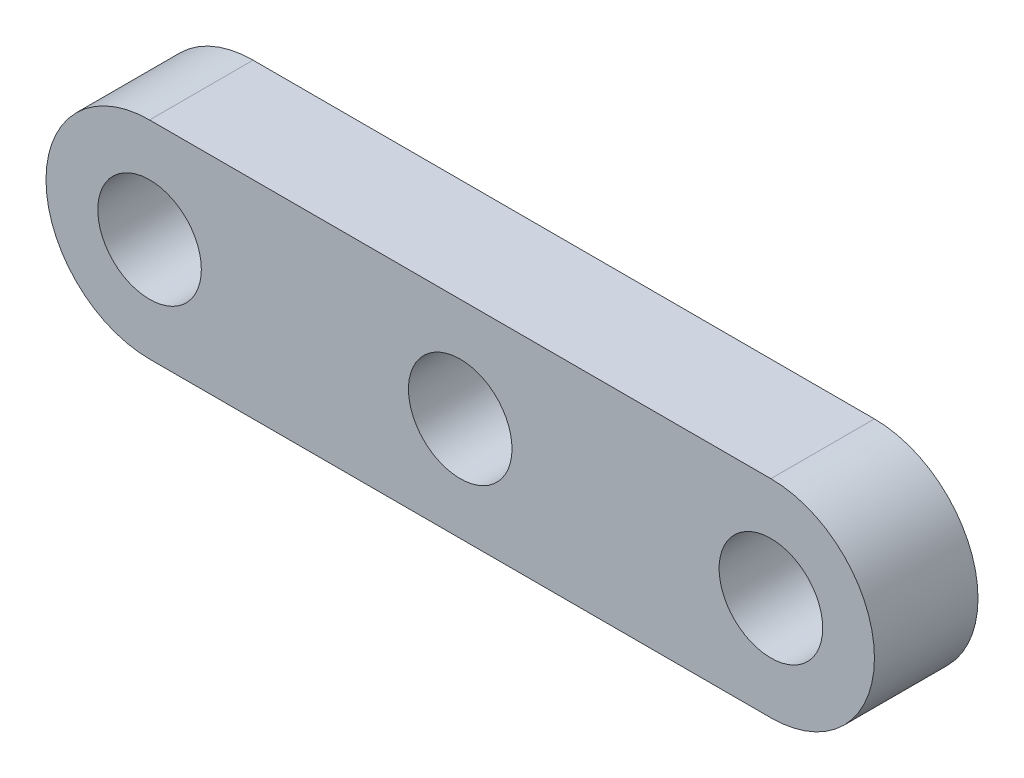
SolidWorks part; units mm, degrees
material "ABS"
ref_plane "Front Plane" through (0, 0, 0) normal (0, 0, 1) x (1, 0, 0)
ref_plane "Top Plane" through (0, 0, 0) normal (0, 1, 0) x (1, 0, 0)
ref_plane "Right Plane" through (0, 0, 0) normal (1, 0, 0) x (0, 0, -1)
sketch "Sketch2" plane through (0, 0, 0) normal (0, 0, 1) x (1, 0, 0)
  line L0 (19.05, 0) -> (-19.05, 0) construction
  line L1 (19.05, -6.35) -> (-19.05, -6.35)
  line L2 (19.05, 6.35) -> (-19.05, 6.35)
  arc A0 (19.05, -6.35) -> (19.05, 6.35) centre (19.05, 0) ccw
  arc A1 (-19.05, 6.35) -> (-19.05, -6.35) centre (-19.05, 0) ccw
  point P2 (0, 0)
  dimension "D1" = 38.1
  dimension "D2" = 12.7
extrude "Boss-Extrude1" add sketch "Sketch2" along normal blind 6.35
sketch "Sketch3" plane through (0, 0, 6.35) normal (0, 0, 1) x (1, 0, 0)
  circle A0 centre (-19.05, 0) radius 3.175
  circle A1 centre (0, 0) radius 3.175
  circle A2 centre (19.05, 0) radius 3.175
  dimension "D1" = 6.35
  dimension "D2" = 6.35
  dimension "D3" = 6.35
extrude "Cut-Extrude1" cut sketch "Sketch3" against normal through all
